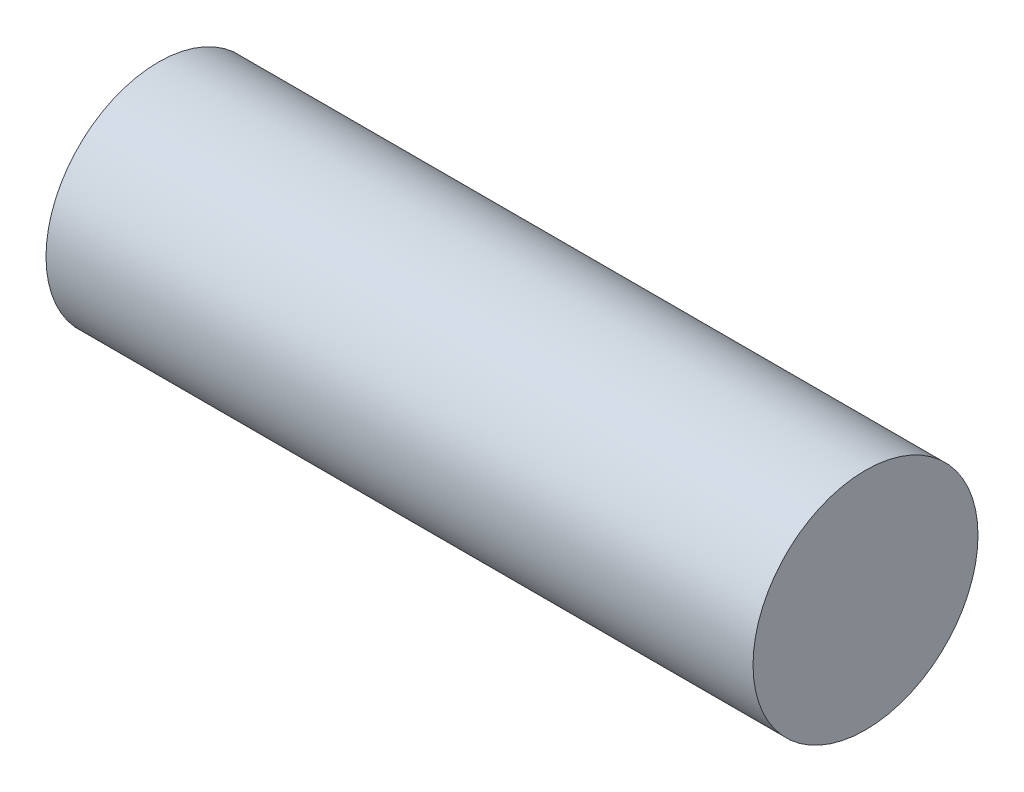
SolidWorks part; units mm, degrees
ref_plane "Front Plane" through (0, 0, 0) normal (0, 0, 1) x (1, 0, 0)
ref_plane "Top Plane" through (0, 0, 0) normal (0, 1, 0) x (1, 0, 0)
ref_plane "Right Plane" through (0, 0, 0) normal (1, 0, 0) x (0, 0, -1)
sketch "Sketch1" plane through (0, 0, 0) normal (1, 0, 0) x (0, 0, -1)
  circle A0 centre (0, 0) radius 1.75
  dimension "D1" = 3.5
extrude "Boss-Extrude1" add sketch "Sketch1" along normal mid plane 11
